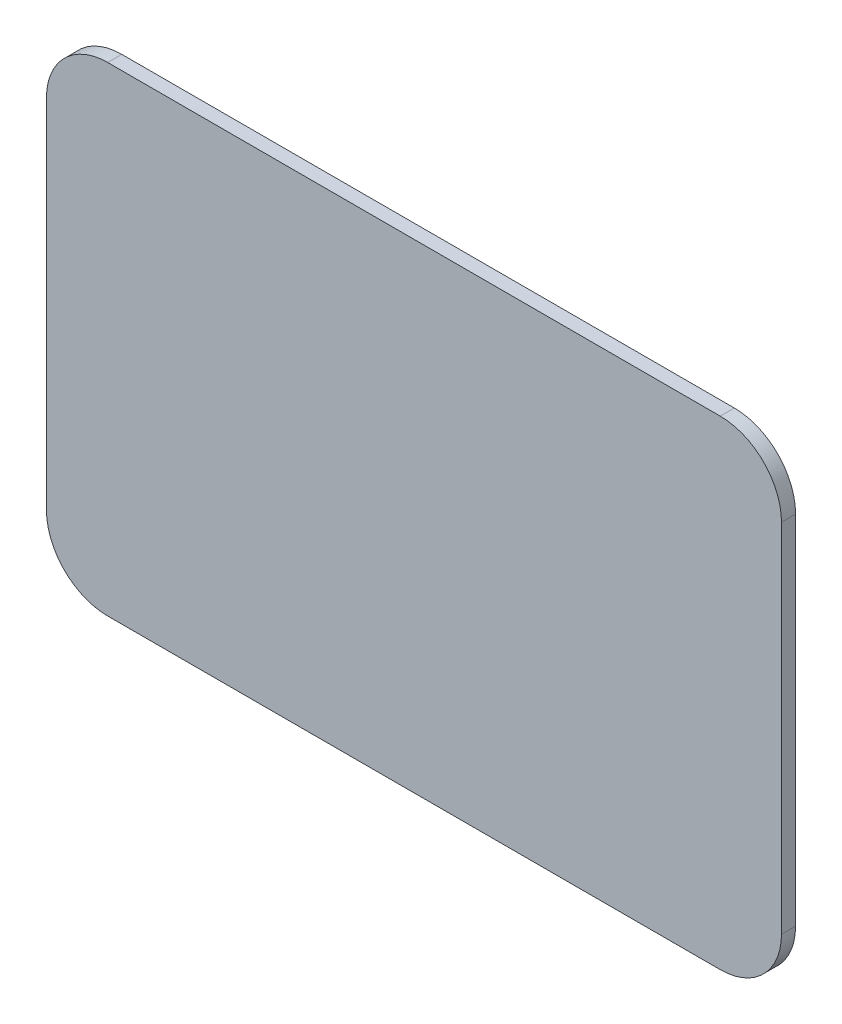
SolidWorks part; units mm, degrees
ref_plane "Front Plane" through (0, 0, 0) normal (0, 0, 1) x (1, 0, 0)
ref_plane "Top Plane" through (0, 0, 0) normal (0, 1, 0) x (1, 0, 0)
ref_plane "Right Plane" through (0, 0, 0) normal (1, 0, 0) x (0, 0, -1)
sketch "Sketch1" plane through (0, 0, 0) normal (0, 0, 1) x (1, 0, 0)
  line L1 (250, 195.65) -> (-250, 195.65)
  line L2 (300, 145.65) -> (300, -145.65)
  line L3 (250, -195.65) -> (-250, -195.65)
  line L4 (-300, 145.65) -> (-300, -145.65)
  line L5 (300, 195.65) -> (-300, -195.65) construction
  line L6 (300, -195.65) -> (-300, 195.65) construction
  arc A0 (-300, -145.65) -> (-250, -195.65) centre (-250, -145.65) ccw
  arc A1 (250, -195.65) -> (300, -145.65) centre (250, -145.65) ccw
  arc A2 (250, 195.65) -> (300, 145.65) centre (250, 145.65) cw
  arc A3 (-300, 145.65) -> (-250, 195.65) centre (-250, 145.65) cw
  point P0 (0, 0)
  dimension "D3" = 50
  dimension "D1" = 600
  dimension "D2" = 391.3
extrude "Boss-Extrude1" add sketch "Sketch1" along normal blind 1.5 and the other way blind 10
